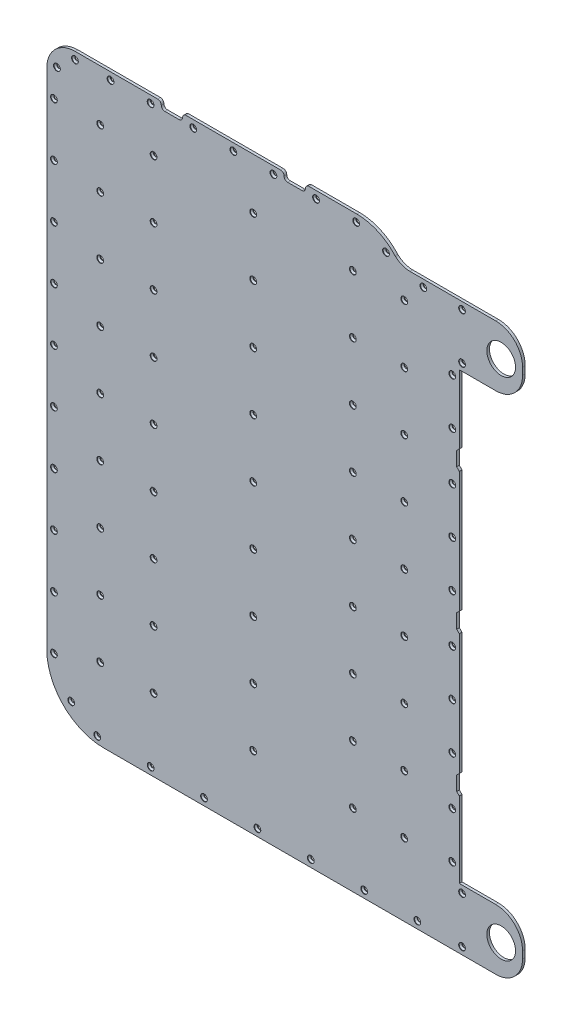
SolidWorks part; units mm, degrees
ref_plane "Front Plane" through (0, 0, 0) normal (0, 0, 1) x (1, 0, 0)
ref_plane "Top Plane" through (0, 0, 0) normal (0, 1, 0) x (1, 0, 0)
ref_plane "Right Plane" through (0, 0, 0) normal (1, 0, 0) x (0, 0, -1)
ref_plane "Plane1" through (0, 0, 1.5) normal (0, 0, 1) x (1, 0, 0)
sketch "Sketch1" plane through (0, 0, 1.5) normal (0, 0, 1) x (1, 0, 0)
  line L0 (267.3541, 331) -> (0, 331)
  line L1 (0, 331) -> (0, 0)
  line L2 (0, 0) -> (267.3541, 0)
  line L3 (267.3541, 0) -> (267.3541, 331)
extrude "Boss-Extrude1" add sketch "Sketch1" against normal blind 1.5
sketch "Sketch2" plane through (0, 0, 0) normal (0, 0, -1) x (-1, 0, 0)
  line L0 (-267.3541, 284) -> (-267.3541, 33.9844)
  line L1 (-267.3541, 33.9844) -> (-231.8079, 33.9844)
  line L2 (-231.8079, 33.9844) -> (-231.8148, 76.5759)
  line L3 (-231.8148, 76.5759) -> (-230.3541, 78)
  line L4 (-230.3541, 78) -> (-230.3541, 86)
  line L5 (-230.3541, 86) -> (-231.8165, 87.5)
  line L6 (-231.8165, 87.5) -> (-231.8274, 155.5)
  line L7 (-231.8274, 155.5) -> (-230.3541, 157)
  line L8 (-230.3541, 157) -> (-230.3541, 165)
  line L9 (-230.3541, 165) -> (-231.8292, 166.5)
  line L10 (-231.8292, 166.5) -> (-231.8401, 234.5)
  line L11 (-231.8401, 234.5) -> (-230.3541, 236)
  line L12 (-230.3541, 236) -> (-230.3541, 244)
  line L13 (-230.3541, 244) -> (-231.8419, 245.5)
  line L14 (-231.8419, 245.5) -> (-231.8481, 284)
  line L15 (-231.8481, 284) -> (-267.3541, 284)
extrude "Cut-Extrude1" cut sketch "Sketch2" against normal through all
sketch "Sketch3" plane through (0, 0, 0) normal (0, 0, -1) x (-1, 0, 0)
  line L0 (-174.2254, 331) -> (-267.3541, 331)
  line L1 (-267.3541, 331) -> (-267.3541, 318)
  line L2 (-267.3541, 318) -> (-199.4999, 318)
  line L3 (-199.4999, 318) -> (-195.6927, 321.4126)
  arc A0 (-195.6927, 321.4126) -> (-174.2254, 331) centre (-174.1533, 302.0108) cw
extrude "Cut-Extrude2" cut sketch "Sketch3" against normal through all
sketch "Sketch4" plane through (0, 0, 0) normal (0, 0, -1) x (-1, 0, 0)
  line L0 (-131.3541, 331) -> (-147.3541, 331)
  line L1 (-143.3541, 327) -> (-135.3541, 327)
  arc A0 (-147.3541, 331) -> (-145.3541, 329) centre (-147.3541, 329) cw
  arc A1 (-145.3541, 329) -> (-143.3541, 327) centre (-143.3541, 329) ccw
  arc A2 (-135.3541, 327) -> (-133.3541, 329) centre (-135.3541, 329) ccw
  arc A3 (-133.3541, 329) -> (-131.3541, 331) centre (-131.3541, 329) cw
extrude "Cut-Extrude3" cut sketch "Sketch4" against normal through all
sketch "Sketch5" plane through (0, 0, 0) normal (0, 0, -1) x (-1, 0, 0)
  line L0 (-62.3259, 331) -> (-78.3259, 331)
  line L1 (-74.3259, 327) -> (-66.3259, 327)
  arc A0 (-78.3259, 331) -> (-76.3259, 329) centre (-78.3259, 329) cw
  arc A1 (-76.3259, 329) -> (-74.3259, 327) centre (-74.3259, 329) ccw
  arc A2 (-66.3259, 327) -> (-64.3259, 329) centre (-66.3259, 329) ccw
  arc A3 (-64.3259, 329) -> (-62.3259, 331) centre (-62.3259, 329) cw
extrude "Cut-Extrude4" cut sketch "Sketch5" against normal through all
hole_wizard "M14 Clearance Hole1" positions "Sketch7" profile "Sketch6" hole size "M14" standard "ANSI Metric"
sketch "Sketch7" plane through (0, 0, 1.5) normal (0, 0, 1) x (1, 0, 0)
  point P0 (255.3541, 16.9922)
  point P1 (255.3541, 301.0078)
sketch "Sketch6" plane through (255.3541, 16.9922, 1.5) normal (1, 0, 0) x (0, -1, 0)
  line L0 (0, 0) -> (0, 1.5)
  line L1 (0, 1.5) -> (8.075, 1.5)
  line L2 (8.075, 1.5) -> (8.075, 0)
  line L5 (8.075, 0) -> (0, 0)
  line L11 (0, -6.35) -> (0, 107.95) construction
  dimension "Thru Hole Dia." = 16.15
  dimension "Thru Hole Depth" = 1.5
hole_wizard "CSK for M2 Flat Head Machine Screw1" positions "Sketch9" profile "Sketch8" countersink size "M2" standard "ANSI Metric"
sketch "Sketch9" plane through (0, 0, 1.5) normal (0, 0, 1) x (1, 0, 0)
  point P0 (178.3541, 4)
  point P1 (116, 106.1)
  point P2 (60, 236.9)
  point P3 (30, 138.8)
  point P4 (118.3541, 4)
  point P5 (28.3541, 4)
  point P6 (227.8315, 95.5)
  point P7 (30, 269.6)
  point P8 (116, 236.9)
  point P9 (227.8399, 147.5)
  point P10 (172, 171.5)
  point P11 (58.3541, 4)
  point P12 (30, 171.5)
  point P13 (200.8329, 73.4)
  point P14 (4, 242)
  point P15 (60, 40.7)
  point P16 (4, 152)
  point P17 (13.7, 13.5)
  point P18 (15.8259, 326.8572)
  point P19 (227.8442, 174.5)
  point P20 (200.8592, 236.9)
  point P21 (4, 302)
  point P22 (151.3173, 326.8572)
  point P23 (173.8541, 326.8572)
  point P24 (200.8644, 269.6)
  point P25 (233.3541, 314)
  point P26 (190.6047, 320.573)
  point P27 (227.8526, 226.5)
  point P28 (30, 106.1)
  point P29 (227.8611, 279.5)
  point P30 (172, 236.9)
  point P31 (227.823, 42.5)
  point P32 (116, 269.6)
  point P33 (35.8259, 326.8572)
  point P34 (172, 302.3)
  point P35 (116, 302.3)
  point P36 (116, 171.5)
  point P37 (116, 138.8)
  point P38 (4, 32)
  point P39 (5.7053, 318.108)
  point P40 (172, 204.2)
  point P41 (200.8277, 40.7)
  point P42 (172, 73.4)
  point P43 (60, 106.1)
  point P44 (4, 272)
  point P45 (127.3541, 326.8572)
  point P46 (60, 138.8)
  point P47 (4, 212)
  point P48 (233.3541, 29.9844)
  point P49 (227.8272, 68.5)
  point P50 (60, 73.4)
  point P51 (200.8697, 302.3)
  point P52 (200.8434, 138.8)
  point P53 (82.3541, 326.8572)
  point P54 (104.8541, 326.8572)
  point P55 (60, 302.3)
  point P56 (58.3259, 326.8572)
  point P57 (116, 204.2)
  point P58 (88.3541, 4)
  point P59 (30, 40.7)
  point P60 (116, 73.4)
  point P61 (233.3541, 288)
  point P62 (211.6057, 314)
  point P63 (227.8569, 253.5)
  point P64 (200.8539, 204.2)
  point P65 (227.8484, 200.5)
  point P66 (200.8487, 171.5)
  point P67 (60, 269.6)
  point P68 (172, 269.6)
  point P69 (60, 171.5)
  point P70 (4, 122)
  point P71 (148.3541, 4)
  point P72 (4, 62)
  point P73 (116, 40.7)
  point P74 (4, 92)
  point P75 (30, 204.2)
  point P76 (30, 236.9)
  point P77 (172, 106.1)
  point P78 (227.8357, 121.5)
  point P79 (200.8382, 106.1)
  point P80 (4, 182)
  point P81 (60, 204.2)
  point P82 (172, 40.7)
  point P83 (208.2291, 4)
  point P84 (172, 138.8)
  point P85 (30, 73.4)
  point P86 (233.3541, 4)
  point P87 (30, 302.3)
sketch "Sketch8" plane through (178.3541, 4, 1.5) normal (1, 0, 0) x (0, -1, 0)
  line L0 (0, 0) -> (0, 1.5)
  line L1 (0, 1.5) -> (1.1, 1.5)
  line L2 (1.1, 1.5) -> (1.1, 1.1)
  line L3 (1.1, 1.1) -> (1.9, 0.3)
  line L4 (1.9, 0.3) -> (1.9, 0)
  line L6 (1.9, 0) -> (0, 0)
  line L7 (-1.1, 1.1) -> (-1.9, 0.3) construction
  line L11 (0, -6.35) -> (0, 107.95) construction
  dimension "Thru Hole Dia." = 2.2
  dimension "Thru Hole Depth" = 1.5
  dimension "C'Sink Dia." = 3.8
  dimension "C'Sink Angle" = 90
  dimension "Head Clearance" = 0.3
fillet "Fillet1" radius 12 1 edges at (199.4999, 318, 0.75)
fillet "Fillet2" radius 16 1 edges at (0, 331, 0.75)
fillet "Fillet3" radius 32 1 edges at (0, 0, 0.75)
fillet "Fillet4" radius 15 4 edges at (267.3541, 318, 0.75) (267.3541, 284, 0.75) (267.3541, 33.9844, 0.75) (267.3541, 0, 0.75)
